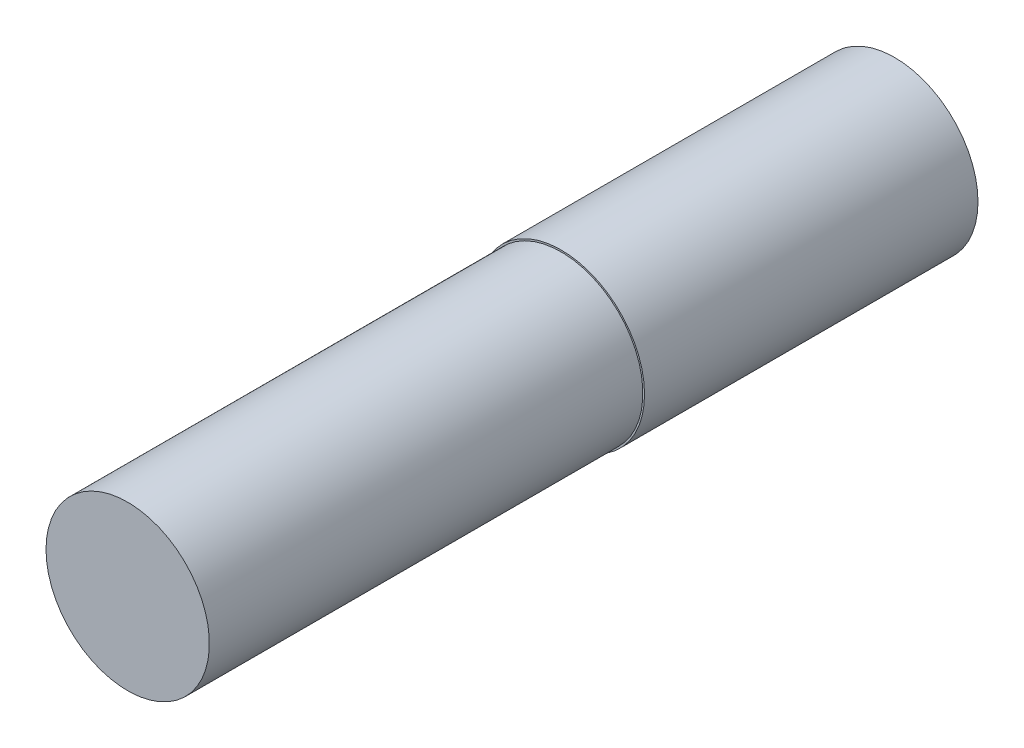
SolidWorks part; units mm, degrees
ref_plane "Plan de face" through (0, 0, 0) normal (0, 0, 1) x (1, 0, 0)
ref_plane "Plan de dessus" through (0, 0, 0) normal (0, 1, 0) x (1, 0, 0)
ref_plane "Plan de droite" through (0, 0, 0) normal (1, 0, 0) x (0, 0, -1)
sketch "Esquisse1" plane through (0, 0, 0) normal (0, 0, 1) x (1, 0, 0)
  circle A0 centre (0, 0) radius 2.5
  dimension "D1" = 5
extrude "Boss.-Extru.1" add sketch "Esquisse1" along normal blind 10
sketch "Esquisse2" plane through (0, 0, 10) normal (0, 0, 1) x (1, 0, 0)
  circle A0 centre (0, 0) radius 2.45
  dimension "D1" = 4.9
extrude "Boss.-Extru.2" add sketch "Esquisse2" along normal blind 13
